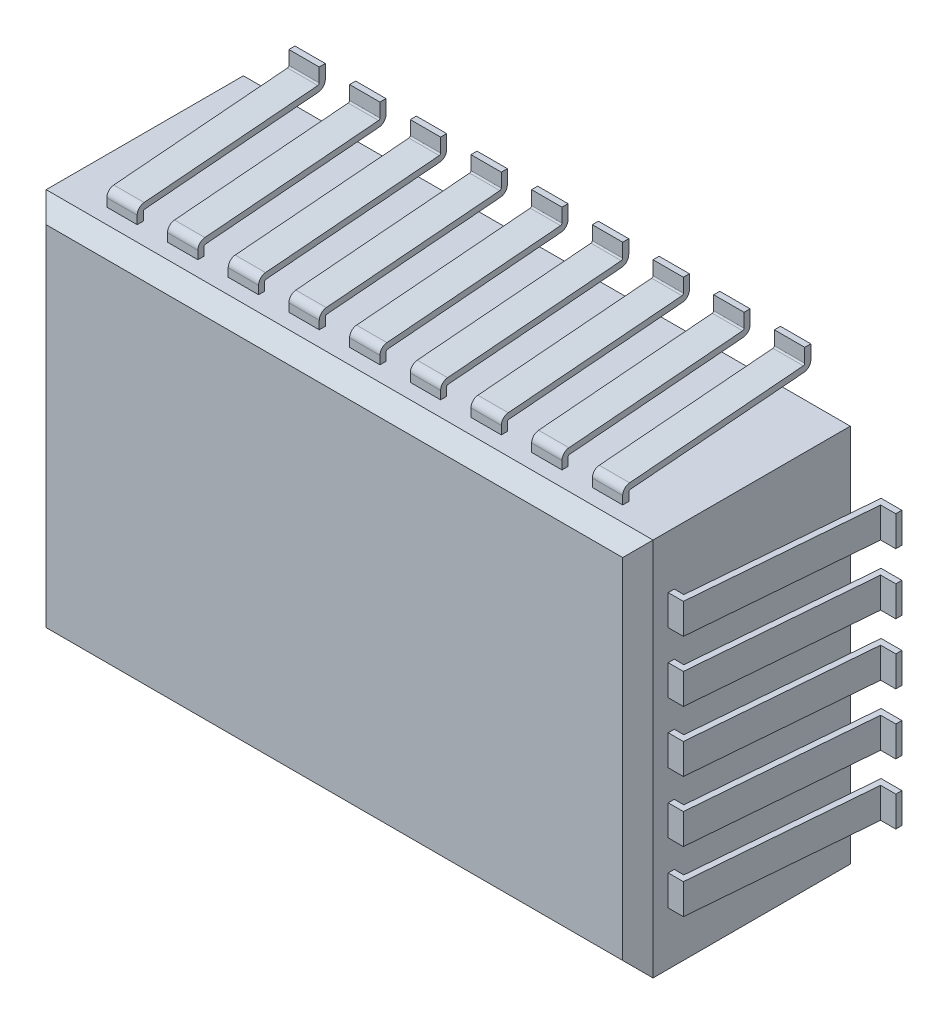
SolidWorks part; units mm, degrees
ref_plane "Front" through (0, 0, 0) normal (0, 0, 1) x (1, 0, 0)
ref_plane "Top" through (0, 0, 0) normal (0, 1, 0) x (1, 0, 0)
ref_plane "Right" through (0, 0, 0) normal (1, 0, 0) x (0, 0, -1)
sketch "COMPONENT_OUTLINE" plane through (0, 0, 0) normal (0, 0, 1) x (1, 0, 0)
  line L0 (-2, 1.25) -> (-2, -1.25)
  line L1 (-2, -1.25) -> (2, -1.25)
  line L2 (2, -1.25) -> (2, 1.25)
  line L3 (2, 1.25) -> (-2, 1.25)
  line L4 (-2, 1.25) -> (2, -1.25) construction
  line L5 (-2, -1.25) -> (2, 1.25) construction
  dimension "D1" = 2.5
  dimension "D2" = 4
extrude "Extrude1" add sketch "COMPONENT_OUTLINE" along normal blind 1.4
sketch "Sketch1" plane through (0, 0, 0) normal (1, 0, 0) x (0, 0, -1)
  line L0 (-1.2, 1.25) -> (-1.2, 1.35)
  line L1 (-1.4, 1.25) -> (0, 1.25) construction
  line L2 (-1.2, 1.35) -> (0, 1.45)
  line L3 (0, 1.45) -> (0, 1.55)
  dimension "D1" = 0.1
  dimension "D2" = 0.2
  dimension "D3" = 0.2
  dimension "D4" = 0.1
extrude "Extrude-Thin1" add sketch "Sketch1" along normal mid plane 0.2 thin
pattern_linear "LPattern1" count 5 spacing 0.4 along (-1, 0, 0) count 5 spacing 0.4 along (1, 0, 0) of "Extrude-Thin1"
mirror "Mirror1" about plane through (0, 0, 0) normal (0, 1, 0) of "Extrude-Thin1", "LPattern1"
sketch "Sketch2" plane through (0, 0, 0) normal (0, 1, 0) x (1, 0, 0)
  line L0 (2, -1.2) -> (2.1, -1.2)
  line L1 (2, -1.4) -> (2, 0) construction
  line L2 (2.1, -1.2) -> (2.2, 0)
  line L3 (2.2, 0) -> (2.3, 0)
  line L4 (2, -1.4) -> (-2, -1.4) construction
  dimension "D1" = 0.1
  dimension "D2" = 0.2
  dimension "D3" = 0.2
  dimension "D4" = 0.1
extrude "Extrude-Thin2" add sketch "Sketch2" along normal mid plane 0.2 thin thin type one direction reverse wall 0.04
pattern_linear "LPattern2" count 3 spacing 0.4 along (0, 1, 0) count 3 spacing 0.4 along (0, -1, 0) of "Extrude-Thin2"
mirror "Mirror2" about plane through (0, 0, 0) normal (1, 0, 0) of "LPattern2", "Extrude-Thin2"
chamfer "Chamfer1" distance 0.1 angle 45 4 edges at (2, 0, 1.4) (0, -1.25, 1.4) (-2, 0, 1.4) (0, 1.25, 1.4)
